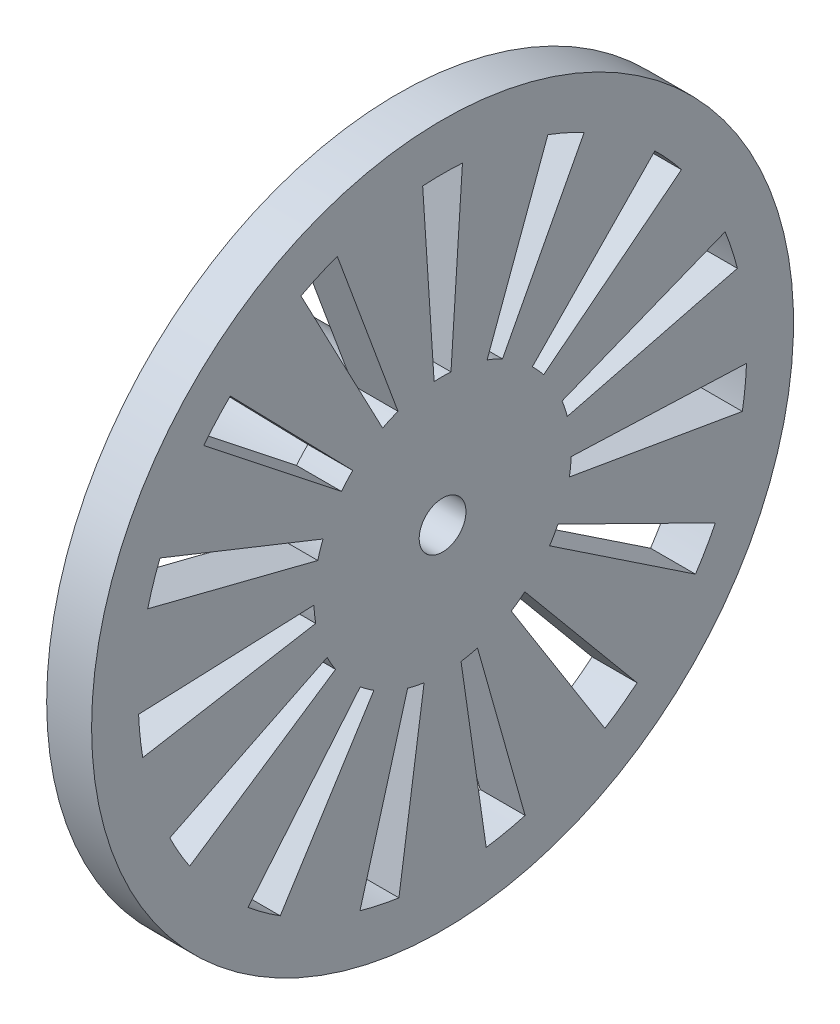
SolidWorks part; units mm, degrees
ref_plane "Front Plane" through (0, 0, 0) normal (0, 0, 1) x (1, 0, 0)
ref_plane "Top Plane" through (0, 0, 0) normal (0, 1, 0) x (1, 0, 0)
ref_plane "Right Plane" through (0, 0, 0) normal (1, 0, 0) x (0, 0, -1)
sketch "Sketch1" plane through (0, 0, 0) normal (0, 0, 1) x (1, 0, 0)
  line L0 (-1851.4839, 0) -> (90763.3287, 0) construction
  line L1 (0, 0.5) -> (4.46, 0.5)
  line L2 (4.46, 0.5) -> (4.46, 7.5)
  line L3 (4.46, 7.5) -> (3.5, 7.5)
  line L4 (3.5, 7.5) -> (3.5, 1.75)
  line L5 (3.5, 1.75) -> (0, 1.75)
  line L6 (0, 1.75) -> (0, 0.5)
  point P1 (0, 0)
  dimension "D1" = 15
  dimension "D2" = 0.96
  dimension "D3" = 3.5
  dimension "D4" = 1
  dimension "D5" = 3.5
revolve "Revolve1" add sketch "Sketch1" angle 360 about L0
sketch "Sketch2" plane through (4.46, 0, 0) normal (1, 0, 0) x (0, 0, -1)
  line L0 (-0.4251, 6.4861) -> (-0.1799, 2.7441)
  line L1 (0.1799, 2.7441) -> (0.4251, 6.4861)
  arc A0 (-0.1799, 2.7441) -> (0.1799, 2.7441) centre (0, 0) cw
  arc A1 (-0.4251, 6.4861) -> (0.4251, 6.4861) centre (0, 0) cw
  circle A2 centre (0, 0) radius 7.5 construction
  circle A3 centre (0, 0) radius 1.75 construction
  point P6 (0, 2.75)
  point P7 (0, 6.5)
  dimension "D1" = 1
  dimension "D2" = 1
  dimension "D3" = 7.5
extrude "Cut-Extrude1" cut sketch "Sketch2" against normal through all
pattern_circular "CirPattern1" count 15 over 360 about axis through (0, 0, 0) along (1, 0, 0) of "Cut-Extrude1"
